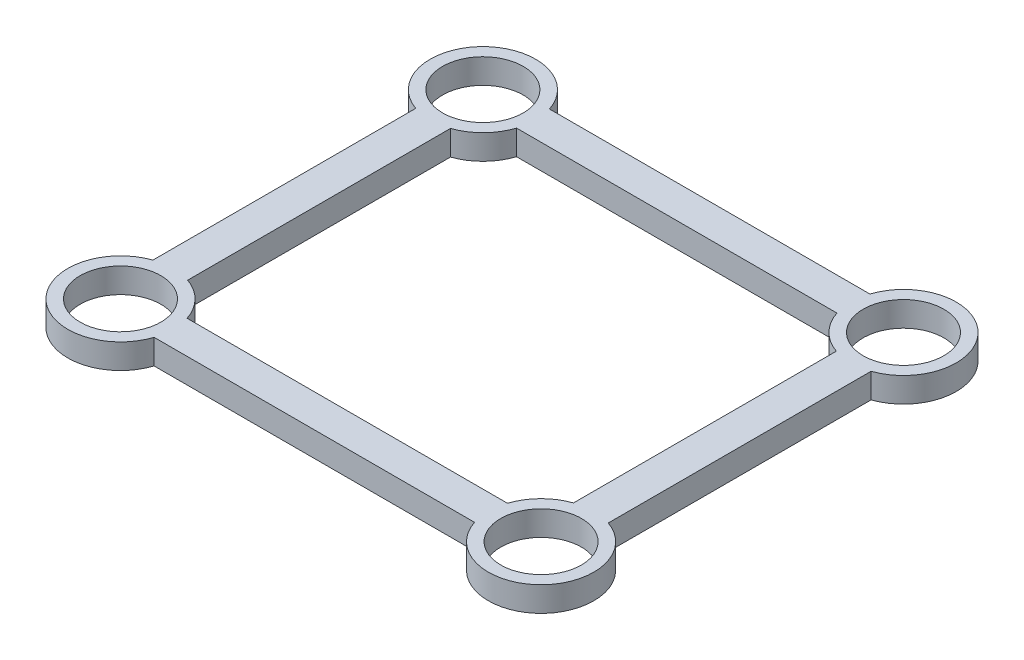
SolidWorks part; units mm, degrees
ref_plane "Front Plane" through (0, 0, 0) normal (0, 0, 1) x (1, 0, 0)
ref_plane "Top Plane" through (0, 0, 0) normal (0, 1, 0) x (1, 0, 0)
ref_plane "Right Plane" through (0, 0, 0) normal (1, 0, 0) x (0, 0, -1)
sketch "Sketch1" plane through (0, 0, 0) normal (0, 1, 0) x (1, 0, 0)
  line L0 (-20.2986, 13.1927) -> (-20.2986, -13.6992)
  line L1 (-16.7412, 13.1927) -> (-16.7412, -13.6992)
  line L2 (24.5162, -18.7953) -> (5.6578, -0.3343) construction
  line L3 (2.9982, 19.9755) -> (2.9982, -20.482) construction
  line L4 (24.5162, 18.2887) -> (5.6578, -0.3343) construction
  line L5 (22.7376, 13.1927) -> (22.7376, -13.6992)
  line L6 (-18.5199, 18.2887) -> (0.3386, -0.3343) construction
  line L7 (-13.3927, 19.9755) -> (19.3891, 19.9755)
  line L8 (-13.3927, 16.602) -> (19.3891, 16.602)
  line L9 (-18.5199, -18.7953) -> (0.3386, -0.3343) construction
  line L10 (26.2949, 13.1927) -> (26.2949, -13.6992)
  line L11 (-18.5199, 18.2887) -> (-18.5199, -18.7953) construction
  line L12 (-20.2986, -13.6992) -> (-16.7412, -13.6992) construction
  line L15 (-13.3927, -17.1085) -> (19.3891, -17.1085)
  line L16 (-13.3927, -20.482) -> (19.3891, -20.482)
  arc A0 (-16.7412, 13.1927) -> (-13.3927, 16.602) centre (-18.5199, 18.2887) ccw
  arc A1 (22.7376, -13.6992) -> (19.3891, -17.1085) centre (24.5162, -18.7953) ccw
  circle A2 centre (24.5162, 18.2887) radius 4.1275
  circle A3 centre (-18.5199, -18.7953) radius 4.1275
  arc A4 (-13.3927, 19.9755) -> (-20.2986, 13.1927) centre (-18.5199, 18.2887) ccw
  arc A5 (19.3891, -20.482) -> (26.2949, -13.6992) centre (24.5162, -18.7953) ccw
  arc A6 (19.3891, 19.9755) -> (26.2949, 13.1927) centre (24.5162, 18.2887) cw
  arc A7 (-13.3927, -20.482) -> (-20.2986, -13.6992) centre (-18.5199, -18.7953) cw
  circle A8 centre (-18.5199, 18.2887) radius 4.1275
  circle A9 centre (24.5162, -18.7953) radius 4.1275
  arc A10 (22.7376, 13.1927) -> (19.3891, 16.602) centre (24.5162, 18.2887) cw
  arc A11 (-16.7412, -13.6992) -> (-13.3927, -17.1085) centre (-18.5199, -18.7953) cw
  point P0 (0, 0)
  point P6 (2.9982, 16.602)
  point P8 (-18.5199, -0.2533)
  point P28 (2.9982, -17.1085)
  dimension "D1" = 8.255
  dimension "D3" = 10.795
  dimension "D6" = 5.3975
  dimension "D4" = 8.255
  dimension "D5" = 37.084
  dimension "D2" = 21.5181
extrude "Boss-Extrude1" add sketch "Sketch1" along normal blind 2.54
